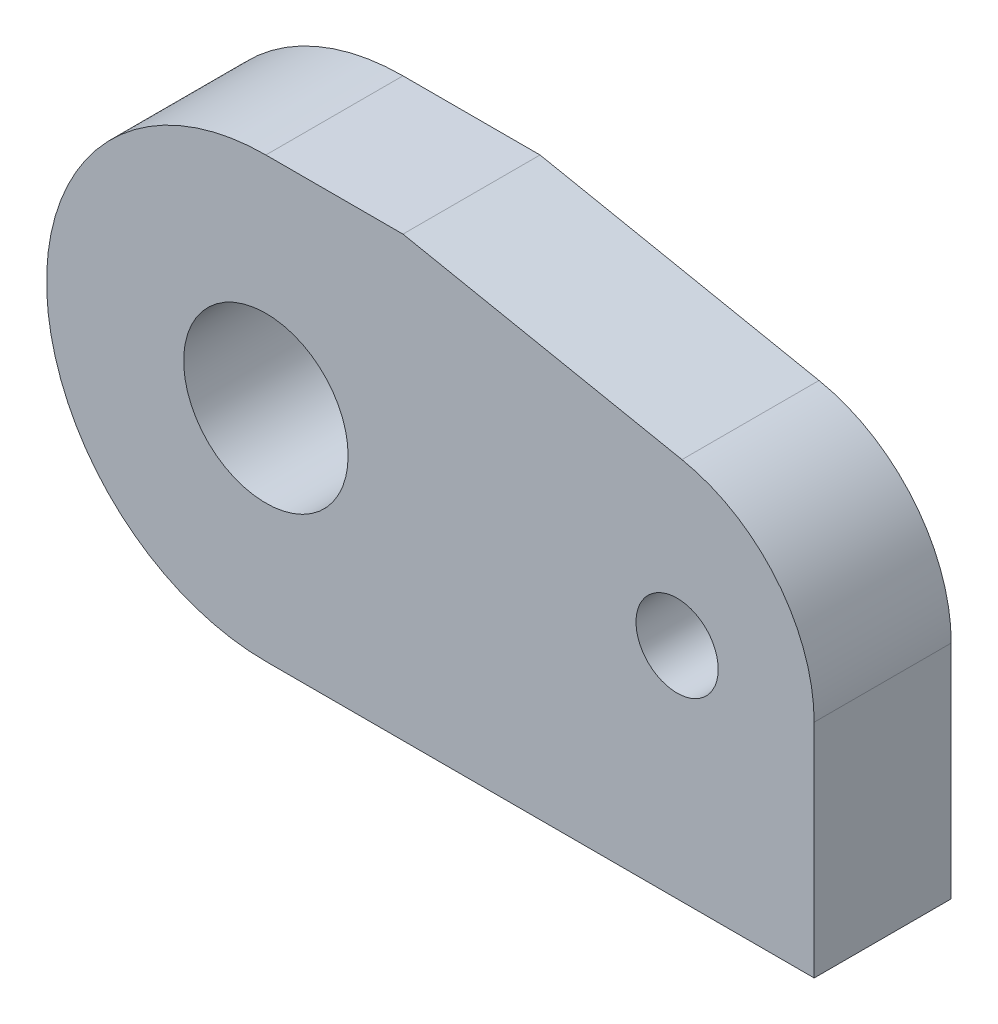
SolidWorks part; units mm, degrees
ref_plane "Plan de face" through (0, 0, 0) normal (0, 0, 1) x (1, 0, 0)
ref_plane "Plan de dessus" through (0, 0, 0) normal (0, 1, 0) x (1, 0, 0)
ref_plane "Plan de droite" through (0, 0, 0) normal (1, 0, 0) x (0, 0, -1)
sketch "Esquisse1" plane through (0, 0, 0) normal (0, 0, 1) x (1, 0, 0)
  line L0 (0, 0) -> (80, 0) construction
  line L1 (20, 0) -> (20, 23.8674) construction
  line L2 (0, 0) -> (0, 35) construction
  line L3 (0, 35) -> (55, 35) construction
  line L4 (0, 8) -> (5, 8)
  line L5 (82.6316, 13.5175) -> (85, 11.6762) construction
  line L6 (20, 8) -> (32.7289, 8) construction
  line L7 (0, -8) -> (55, -8) construction
  line L8 (55, 35) -> (55, -8) construction
  line L9 (0, -8) -> (20, -8)
  line L10 (20, -8) -> (20, 5)
  line L11 (20, 5) -> (5, 8)
  circle A0 centre (0, 0) radius 3
  arc A1 (0, 8) -> (0, -8) centre (0, 0) ccw
  circle A2 centre (55, 35) radius 35 construction
  arc A3 (32.7289, 8) -> (82.6316, 13.5175) centre (55, 35) ccw construction
  arc A4 (82.6316, 13.5175) -> (87.5479, 10.0925) centre (85, 11.6762) cw construction
  arc A5 (55, -8) -> (87.5479, 10.0925) centre (55, 30.3227) ccw construction
  circle A6 centre (15, 0) radius 1.5
  dimension "D3" = 6
  dimension "D4" = 35
  dimension "D6" = 70
  dimension "D7" = 3
  dimension "D8" = 8
  dimension "D9" = 30
  dimension "D10" = 15
  dimension "D14" = 3
  dimension "D1" = 20
  dimension "D2" = 80
  dimension "D5" = 55
  dimension "D11" = 13
  dimension "D12" = 15
  dimension "D13" = 20
extrude "Boss.-Extru.1" add sketch "Esquisse1" along normal blind 5
fillet "Congé1" radius 6 1 edges at (20, 5, 2.5)
